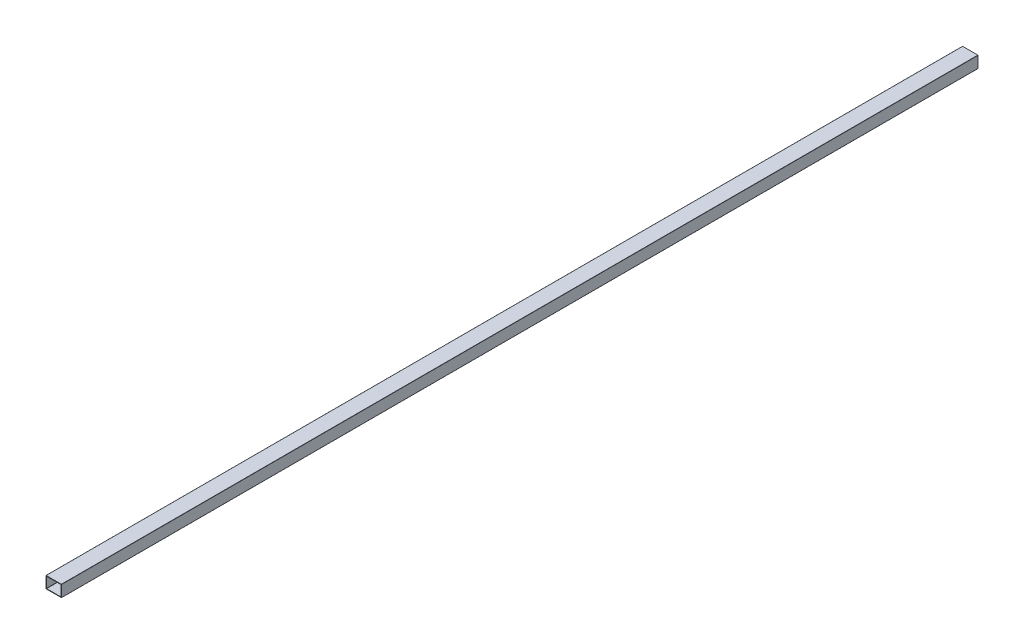
SolidWorks part; units mm, degrees
material "AISI 1035 Acero (SS)"
ref_plane "Alzado" through (0, 0, 0) normal (0, 0, 1) x (1, 0, 0)
ref_plane "Planta" through (0, 0, 0) normal (0, 1, 0) x (1, 0, 0)
ref_plane "Vista lateral" through (0, 0, 0) normal (1, 0, 0) x (0, 0, -1)
sketch "Croquis1" plane through (0, 0, 0) normal (0, 0, 1) x (1, 0, 0)
  line L0 (-47.76, -35.06) -> (-47.76, 35.06)
  line L1 (-50.8, -38.1) -> (50.8, -38.1)
  line L2 (-50.8, -38.1) -> (-50.8, 38.1)
  line L3 (-50.8, 38.1) -> (50.8, 38.1)
  line L4 (50.8, -38.1) -> (50.8, 38.1)
  line L5 (-50.8, -38.1) -> (50.8, 38.1) construction
  line L6 (-50.8, 38.1) -> (50.8, -38.1) construction
  line L7 (-47.76, 35.06) -> (47.76, 35.06)
  line L8 (47.76, -35.06) -> (47.76, 35.06)
  line L9 (-47.76, -35.06) -> (47.76, -35.06)
  point P0 (0, 0)
  dimension "D1" = 76.2
  dimension "D2" = 101.6
  dimension "D3" = 3.04
extrude "Saliente-Extruir1" add sketch "Croquis1" against normal blind 6000
fillet "Redondeo1" radius 1 8 edges at (-47.76, 35.06, -3000) (47.76, 35.06, -3000) (47.76, -35.06, -3000) (-50.8, -38.1, -3000) (-50.8, 38.1, -3000) (-47.76, -35.06, -3000) (50.8, -38.1, -3000) (50.8, 38.1, -3000)
